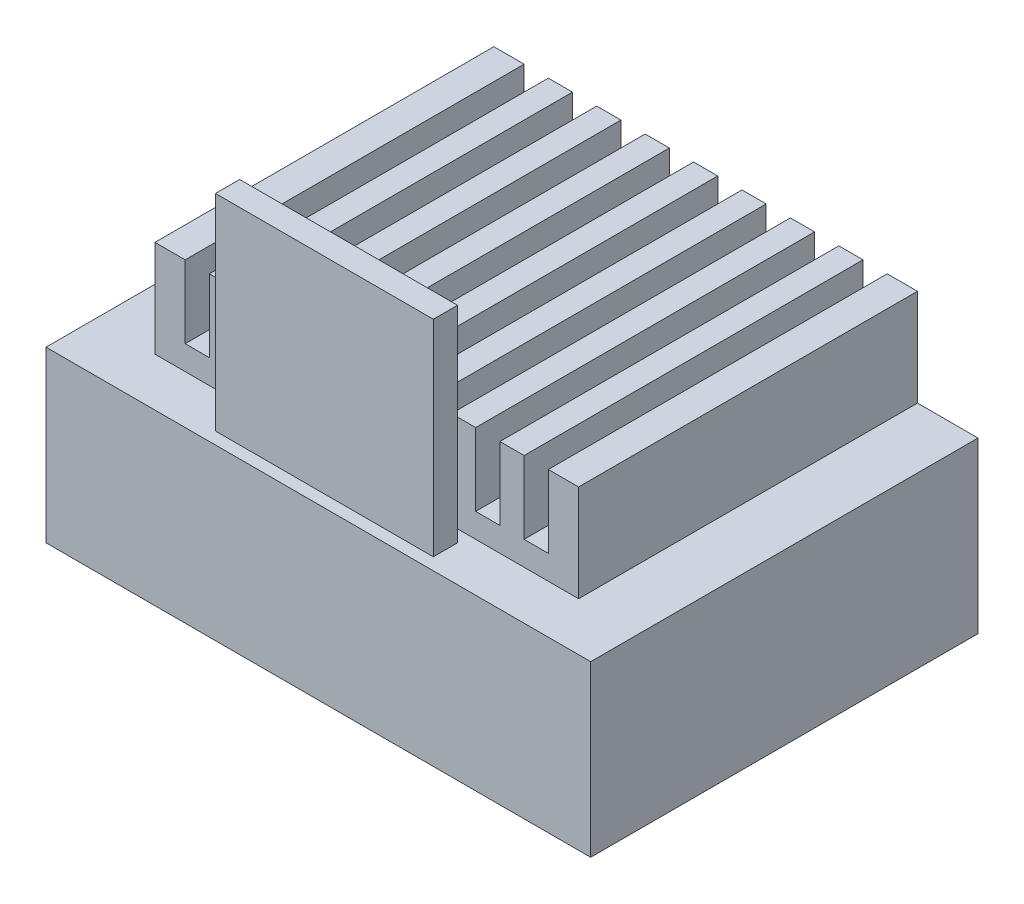
SolidWorks part; units mm, degrees
ref_plane "Front Plane" through (0, 0, 0) normal (0, 0, 1) x (1, 0, 0)
ref_plane "Top Plane" through (0, 0, 0) normal (0, 1, 0) x (1, 0, 0)
ref_plane "Right Plane" through (0, 0, 0) normal (1, 0, 0) x (0, 0, -1)
sketch "Sketch1" plane through (0, 0, 0) normal (0, 1, 0) x (1, 0, 0)
  line L1 (-22.5, -16) -> (22.5, -16)
  line L2 (-22.5, -16) -> (-22.5, 16)
  line L3 (-22.5, 16) -> (22.5, 16)
  line L4 (22.5, -16) -> (22.5, 16)
  line L5 (-22.5, -16) -> (22.5, 16) construction
  line L6 (-22.5, 16) -> (22.5, -16) construction
  point P0 (0, 0)
  dimension "D1" = 45
  dimension "D2" = 32
extrude "Boss-Extrude1" add sketch "Sketch1" against normal blind 14
sketch "Sketch5" plane through (0, 0, 0) normal (0, 1, 0) x (1, 0, 0)
  line L1 (-22.5, -16) -> (22.5, -16) construction
  line L2 (22.5, -16) -> (22.5, 16) construction
  line L3 (22.5, 16) -> (-22.5, 16) construction
  line L5 (-17.5, 16) -> (17.5, 16)
  line L6 (-17.5, 16) -> (-17.5, -12)
  line L7 (-17.5, -12) -> (17.5, -12)
  line L8 (17.5, 16) -> (17.5, -12)
  point P0 (17.5, -12)
  point P7 (-17.5, 16)
  dimension "D2" = 5
  dimension "D3" = 5
  dimension "D1" = 4
extrude "Boss-Extrude2" add sketch "Sketch5" along normal blind 8 separate body
sketch "Sketch8" plane through (0, 8, 0) normal (0, 1, 0) x (1, 0, 0)
  line L0 (17.5, 16) -> (-17.5, 16) construction
  line L1 (-17.5, -12) -> (17.5, -12) construction
  line L3 (-15, 16) -> (-13, 16)
  line L4 (-15, 16) -> (-15, -12)
  line L5 (-15, -12) -> (-13, -12)
  line L6 (-13, 16) -> (-13, -12)
  point P0 (-15, 16)
  point P1 (-13, -12)
  dimension "D1" = 2.5
  dimension "D2" = 4.5
extrude "Cut-Extrude2" cut sketch "Sketch8" against normal blind 6
pattern_linear "LPattern3" count 8 spacing 4 along (1, 0, 0) of "Cut-Extrude2"
sketch "Sketch9" plane through (0, 0, 0) normal (0, 1, 0) x (1, 0, 0)
  line L0 (-22.5, -16) -> (22.5, -16) construction
  line L1 (-22.5, 16) -> (-22.5, -16) construction
  line L3 (-9.5, -15) -> (8.5, -15)
  line L4 (-9.5, -15) -> (-9.5, -13)
  line L5 (-9.5, -13) -> (8.5, -13)
  line L6 (8.5, -15) -> (8.5, -13)
  point P0 (-9.5, -15)
  point P1 (8.5, -13)
  dimension "D1" = 1
  dimension "D2" = 13
  dimension "D3" = 3
  dimension "D4" = 31
extrude "Boss-Extrude3" add sketch "Sketch9" along normal blind 17
